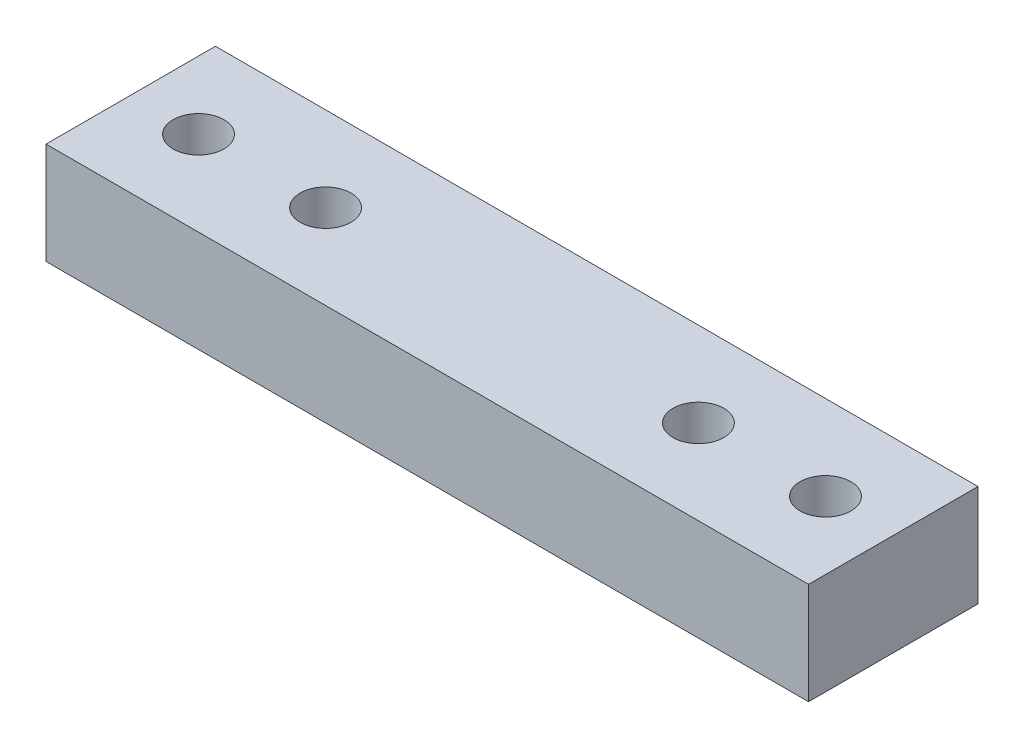
SolidWorks part; units mm, degrees
ref_plane "Front Plane" through (0, 0, 0) normal (0, 0, 1) x (1, 0, 0)
ref_plane "Top Plane" through (0, 0, 0) normal (0, 1, 0) x (1, 0, 0)
ref_plane "Right Plane" through (0, 0, 0) normal (1, 0, 0) x (0, 0, -1)
sketch "Sketch1" plane through (0, 0, 0) normal (0, 1, 0) x (1, 0, 0)
  line L0 (-18.5963, 1.5023) -> (29.5225, 1.5023) construction
  line L1 (-18.5963, 6.5023) -> (26.4037, 6.5023)
  line L2 (-18.5963, 6.5023) -> (-18.5963, -3.4977)
  line L3 (-18.5963, -3.4977) -> (26.4037, -3.4977)
  line L4 (26.4037, 6.5023) -> (26.4037, -3.4977)
  line L5 (3.9037, 6.5023) -> (3.9037, -3.4977) construction
  circle A0 centre (-14.5963, 1.5023) radius 1.5
  circle A1 centre (-7.0963, 1.5023) radius 1.5
  circle A4 centre (22.4037, 1.5023) radius 1.5
  circle A5 centre (14.9037, 1.5023) radius 1.5
  dimension "3mm" = 3
  dimension "D1" = 45
  dimension "D2" = 10
  dimension "D3" = 4
  dimension "D4" = 11.5
extrude "Boss-Extrude1" add sketch "Sketch1" along normal blind 6
